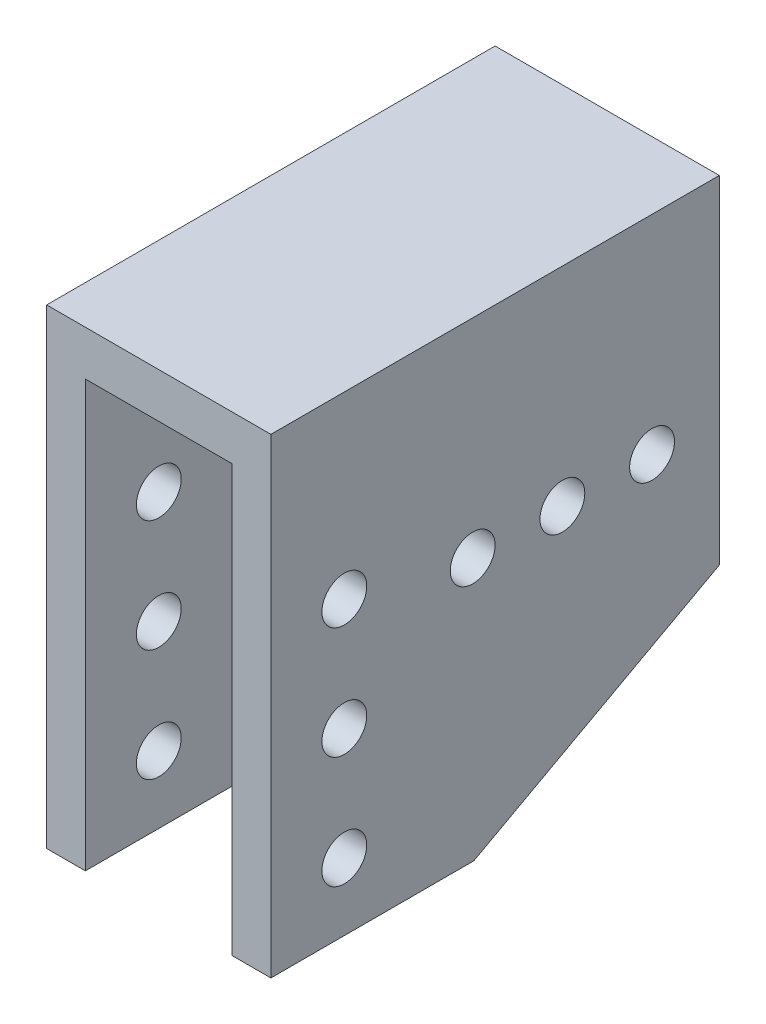
SolidWorks part; units mm, degrees
ref_plane "Front Plane" through (0, 0, 0) normal (0, 0, 1) x (1, 0, 0)
ref_plane "Top Plane" through (0, 0, 0) normal (0, 1, 0) x (1, 0, 0)
ref_plane "Right Plane" through (0, 0, 0) normal (1, 0, 0) x (0, 0, -1)
sketch "Sketch1" plane through (0, 0, 0) normal (0, 1, 0) x (1, 0, 0)
  line L1 (0, 0) -> (20, 0)
  line L2 (0, 0) -> (0, 40)
  line L3 (0, 40) -> (20, 40)
  line L4 (20, 0) -> (20, 40)
  dimension "D1" = 20
  dimension "D2" = 40
extrude "Boss-Extrude1" add sketch "Sketch1" along normal blind 20
sketch "Sketch2" plane through (0, 20, 0) normal (0, 1, 0) x (1, 0, 0)
  line L0 (10, 0) -> (10, 40) construction
  line L1 (0, 0) -> (20, 0) construction
  line L2 (20, 40) -> (0, 40) construction
  line L4 (16.55, 13.1) -> (3.45, 13.1)
  line L5 (16.55, 13.1) -> (16.55, 0)
  line L6 (16.55, 0) -> (3.45, 0)
  line L7 (3.45, 13.1) -> (3.45, 0)
  line L8 (16.55, 13.1) -> (3.45, 0) construction
  line L9 (16.55, 0) -> (3.45, 13.1) construction
  point P6 (10, 6.55)
  dimension "D1" = 13.1
  dimension "D2" = 13.1
extrude "Cut-Extrude1" cut sketch "Sketch2" against normal through all
sketch "Sketch3" plane through (0, 0, -13.1) normal (0, 0, 1) x (1, 0, 0)
  line L0 (16.55, 0) -> (16.55, 20) construction
  line L1 (3.45, 20) -> (16.55, 20)
  line L2 (3.45, 20) -> (3.45, 6.9)
  line L3 (3.45, 6.9) -> (16.55, 6.9)
  line L4 (16.55, 20) -> (16.55, 6.9)
  dimension "D1" = 13.1
extrude "Cut-Extrude2" cut sketch "Sketch3" against normal through all
sketch "Sketch4" plane through (0, 0, 0) normal (0, -1, 0) x (1, 0, 0)
  line L8 (3.45, -13.1) -> (3.45, 0)
  line L9 (3.45, 0) -> (0, 0)
  line L10 (0, 0) -> (0, -40)
  line L11 (0, -40) -> (20, -40)
  line L12 (20, -40) -> (20, 0)
  line L13 (20, 0) -> (16.55, 0)
  line L14 (16.55, 0) -> (16.55, -13.1)
  line L15 (16.55, -13.1) -> (3.45, -13.1)
  line L16 (3.45, -13.1) -> (3.45, 0)
  line L17 (3.45, 0) -> (0, 0)
  line L18 (0, 0) -> (0, -40)
  line L19 (0, -40) -> (20, -40)
  line L20 (20, -40) -> (20, 0)
  line L21 (20, 0) -> (16.55, 0)
  line L22 (16.55, 0) -> (16.55, -13.1)
  line L23 (16.55, -13.1) -> (3.45, -13.1)
  dimension "D1" = 0
extrude "Boss-Extrude2" add sketch "Sketch4" along normal blind 10
sketch "Sketch5" plane through (0, 20, 0) normal (0, 1, 0) x (1, 0, 0)
  line L1 (0, 0) -> (20, 0)
  line L2 (0, 0) -> (0, 40)
  line L3 (0, 40) -> (20, 40)
  line L4 (20, 0) -> (20, 40)
extrude "Boss-Extrude3" add sketch "Sketch5" along normal blind 12
sketch "Sketch6" plane through (0, 0, 0) normal (0, 0, 1) x (1, 0, 0)
  line L0 (3.45, 6.9) -> (16.55, 6.9) construction
  line L1 (3.45, 20) -> (16.55, 20)
  line L2 (3.45, 20) -> (3.45, 28)
  line L3 (3.45, 28) -> (16.55, 28)
  line L4 (16.55, 20) -> (16.55, 28)
  line L5 (3.45, 6.9) -> (16.55, 6.9) construction
  dimension "D1" = 8
extrude "Cut-Extrude3" cut sketch "Sketch6" against normal up to surface (13.1 mm away) up to face at (10, -1.55, -13.1)
sketch "Sketch7" plane through (20, 0, 0) normal (1, 0, 0) x (0, 0, -1)
  line L0 (13.1, -10) -> (13.1, 6.9) construction
  line L1 (13.1, -10) -> (13.1, 6.9) construction
  line L2 (6.55, -10) -> (6.55, 32) construction
  line L3 (40, -10) -> (0, -10) construction
  line L4 (0, 32) -> (40, 32) construction
  line L6 (13.1, -10) -> (0, -10) construction
  circle A0 centre (6.55, -4) radius 2
  circle A1 centre (6.55, 16) radius 2
  circle A2 centre (6.55, 6) radius 2
  dimension "D1" = 4
  dimension "D2" = 6
  dimension "D3" = 10
  dimension "D4" = 10
extrude "Cut-Extrude4" cut sketch "Sketch7" against normal through all
sketch "Sketch8" plane through (3.45, 0, 0) normal (1, 0, 0) x (0, 0, -1)
  line L0 (40, 13.45) -> (0, 13.45) construction
  line L1 (40, 20) -> (40, 6.9) construction
  line L8 (40, 20) -> (13.1, 20)
  line L9 (13.1, 20) -> (13.1, 28)
  line L10 (13.1, 28) -> (0, 28)
  line L11 (0, 28) -> (0, -10)
  line L12 (0, -10) -> (13.1, -10)
  line L13 (13.1, -10) -> (13.1, 6.9)
  line L14 (13.1, 6.9) -> (40, 6.9)
  line L15 (40, 6.9) -> (40, 20)
  line L16 (40, 20) -> (13.1, 20) construction
  line L17 (13.1, 20) -> (13.1, 28) construction
  line L18 (13.1, 28) -> (0, 28) construction
  line L19 (0, 28) -> (0, -10) construction
  line L20 (0, -10) -> (13.1, -10) construction
  line L21 (13.1, -10) -> (13.1, 6.9) construction
  line L22 (13.1, 6.9) -> (40, 6.9) construction
  line L23 (40, 6.9) -> (40, 20) construction
  circle A0 centre (34, 13.45) radius 2
  circle A1 centre (26, 13.45) radius 2
  circle A2 centre (18, 13.45) radius 2
  dimension "D2" = 4
  dimension "D3" = 6
  dimension "D4" = 8
  dimension "D5" = 8
  dimension "D1" = 0
extrude "Cut-Extrude5" cut sketch "Sketch8" against normal through all and the other way through all
sketch "Sketch9" plane through (20, 0, 0) normal (1, 0, 0) x (0, 0, -1)
  line L0 (40, -10) -> (40, 1.9)
  line L1 (40, 32) -> (40, -10) construction
  line L2 (40, 1.9) -> (18.1, -10)
  line L3 (40, -10) -> (0, -10) construction
  line L4 (18.1, -10) -> (40, -10)
  line L5 (13.1, -10) -> (13.1, 6.9) construction
  line L6 (13.1, -10) -> (13.1, 6.9) construction
  line L7 (40, 6.9) -> (40, 20) construction
  line L8 (40, 6.9) -> (40, 20) construction
  line M8 (0, -10) -> (40, -10)
  line M9 (40, -10) -> (40, 32)
  dimension "D1" = 5
  dimension "D2" = 5
extrude "Cut-Extrude6" cut sketch "Sketch9" against normal through all contours L2 M9 M8
